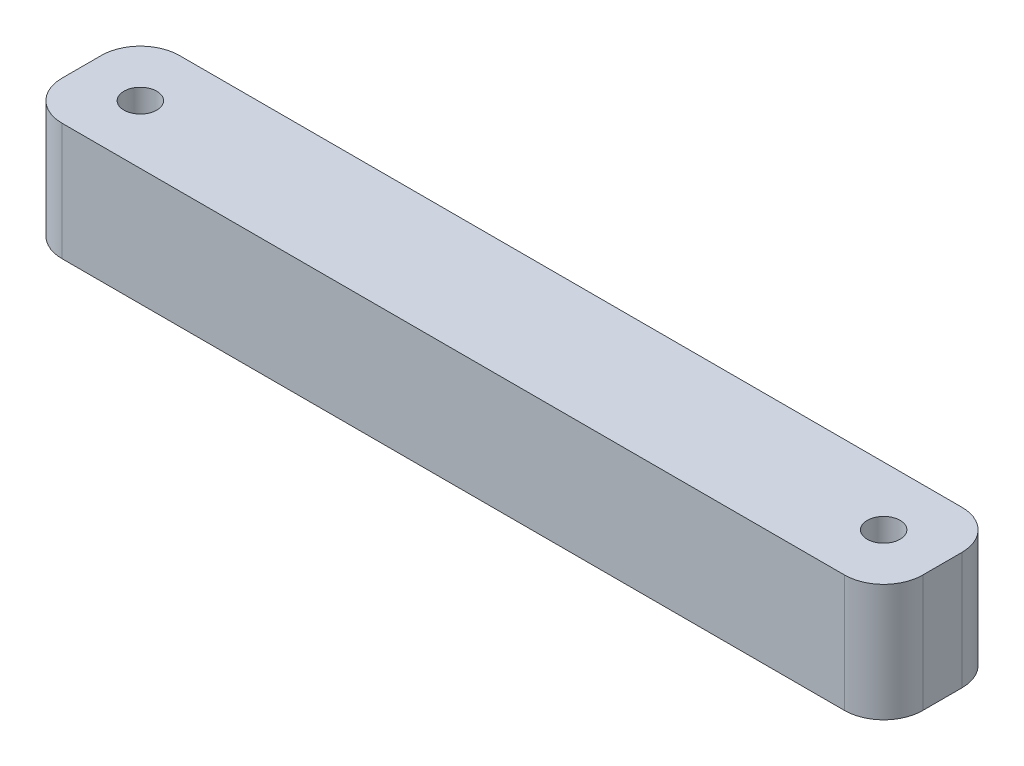
SolidWorks part; units mm, degrees
ref_plane "前视基准面" through (0, 0, 0) normal (0, 0, 1) x (1, 0, 0)
ref_plane "上视基准面" through (0, 0, 0) normal (0, 1, 0) x (1, 0, 0)
ref_plane "右视基准面" through (0, 0, 0) normal (1, 0, 0) x (0, 0, -1)
sketch "草图1" plane through (0, 0, 0) normal (0, 1, 0) x (1, 0, 0)
  line L0 (0, 7.5) -> (7.5, 7.5) construction
  line L1 (0, 0) -> (110, 0)
  line L2 (0, 0) -> (0, 15)
  line L3 (0, 15) -> (110, 15)
  line L4 (110, 0) -> (110, 15)
  line L5 (7.5, 7.5) -> (102.5, 7.5) construction
  line L6 (102.5, 7.5) -> (110, 7.5) construction
  circle A0 centre (7.5, 7.5) radius 2.1
  circle A1 centre (102.5, 7.5) radius 2.1
  dimension "D4" = 4.2
  dimension "D1" = 110
  dimension "D2" = 15
  dimension "D3" = 95
extrude "凸台-拉伸1" add sketch "草图1" along normal blind 15
fillet "圆角1" radius 5 4 edges at (110, 7.5, 0) (110, 7.5, -15) (0, 7.5, -15) (0, 7.5, 0)
